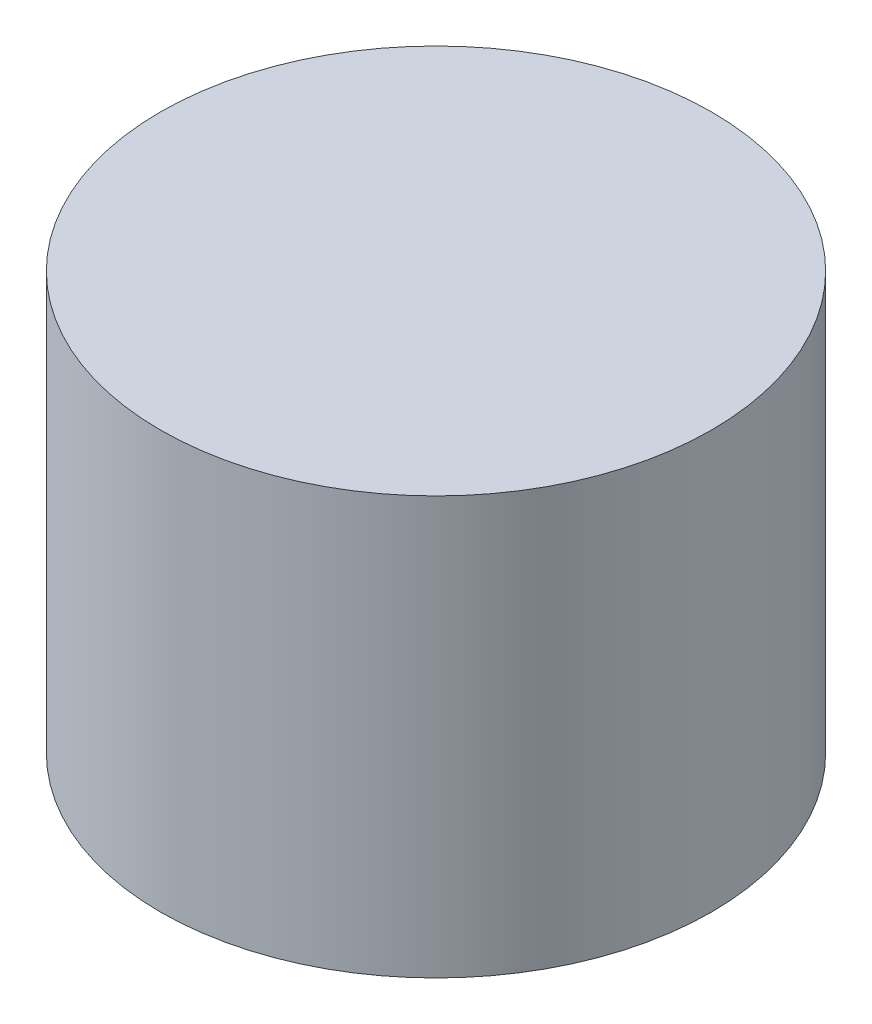
SolidWorks part; units mm, degrees
ref_plane "Спереди" through (0, 0, 0) normal (0, 0, 1) x (1, 0, 0)
ref_plane "Сверху" through (0, 0, 0) normal (0, 1, 0) x (1, 0, 0)
ref_plane "Справа" through (0, 0, 0) normal (1, 0, 0) x (0, 0, -1)
sketch "Эскиз1" plane through (0, 0, 0) normal (0, 1, 0) x (1, 0, 0)
  circle A0 centre (0, 0) radius 66
  dimension "D1" = 132
extrude "Бобышка-Вытянуть1" add sketch "Эскиз1" along normal blind 100
